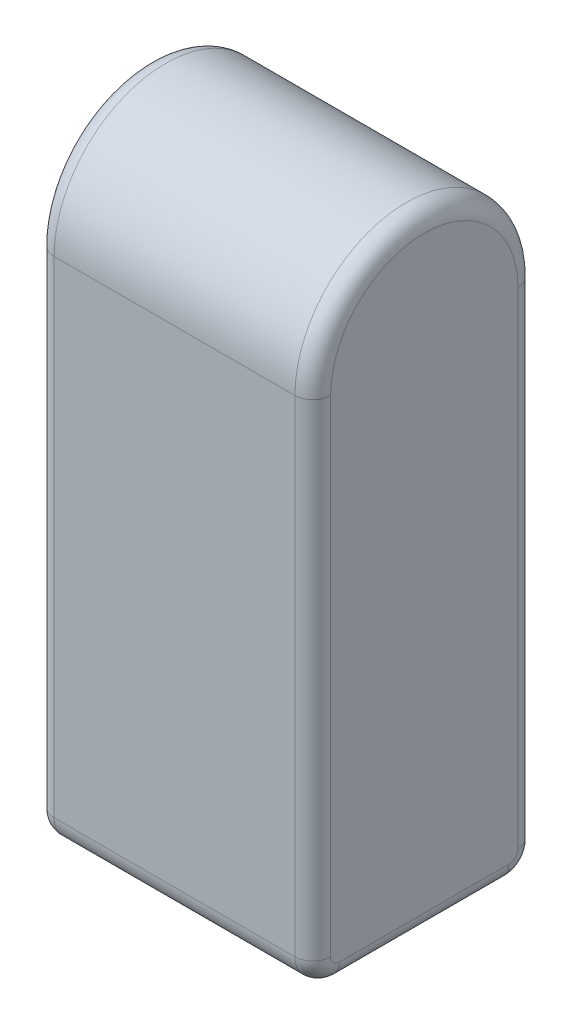
SolidWorks part; units mm, degrees
ref_plane "Front Plane" through (0, 0, 0) normal (0, 0, 1) x (1, 0, 0)
ref_plane "Top Plane" through (0, 0, 0) normal (0, 1, 0) x (1, 0, 0)
ref_plane "Right Plane" through (0, 0, 0) normal (1, 0, 0) x (0, 0, -1)
sketch "Sketch1" plane through (0, 0, 0) normal (1, 0, 0) x (0, 0, -1)
  line L0 (-12.5, 57.5) -> (-12.5, 0)
  line L1 (-12.5, 0) -> (12.5, 0)
  line L2 (12.5, 0) -> (12.5, 57.5)
  arc A0 (-12.5, 57.5) -> (12.5, 57.5) centre (0, 57.5) cw
  point P2 (0, 0)
  point P7 (0, 0)
  point P8 (0, 70)
  dimension "D1" = 25
  dimension "D2" = 70
extrude "Boss-Extrude1" add sketch "Sketch1" along normal mid plane 31
fillet "Fillet1" radius 3 2 edges at (0, 0, -12.5) (0, 0, 12.5)
fillet "Fillet2" radius 2 12 edges at (-15.5, 70, 0) (-15.5, 30.25, -12.5) (-15.5, 0.8787, -11.6213) (-15.5, 0, 0) (-15.5, 0.8787, 11.6213) (15.5, 70, 0) (15.5, 30.25, -12.5) (15.5, 0.8787, -11.6213) (15.5, 0, 0) (15.5, 0.8787, 11.6213) (-15.5, 30.25, 12.5) (15.5, 30.25, 12.5)
